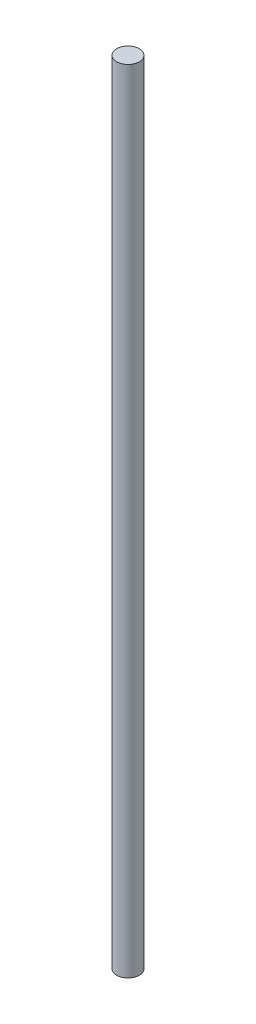
SolidWorks part; units mm, degrees
ref_plane "Front Plane" through (0, 0, 0) normal (0, 0, 1) x (1, 0, 0)
ref_plane "Top Plane" through (0, 0, 0) normal (0, 1, 0) x (1, 0, 0)
ref_plane "Right Plane" through (0, 0, 0) normal (1, 0, 0) x (0, 0, -1)
sketch "Sketch1" plane through (0, 0, 0) normal (0, 1, 0) x (1, 0, 0)
  circle A0 centre (0, 0) radius 4
  dimension "D1" = 8
extrude "Boss-Extrude1" add sketch "Sketch1" along normal blind 280
